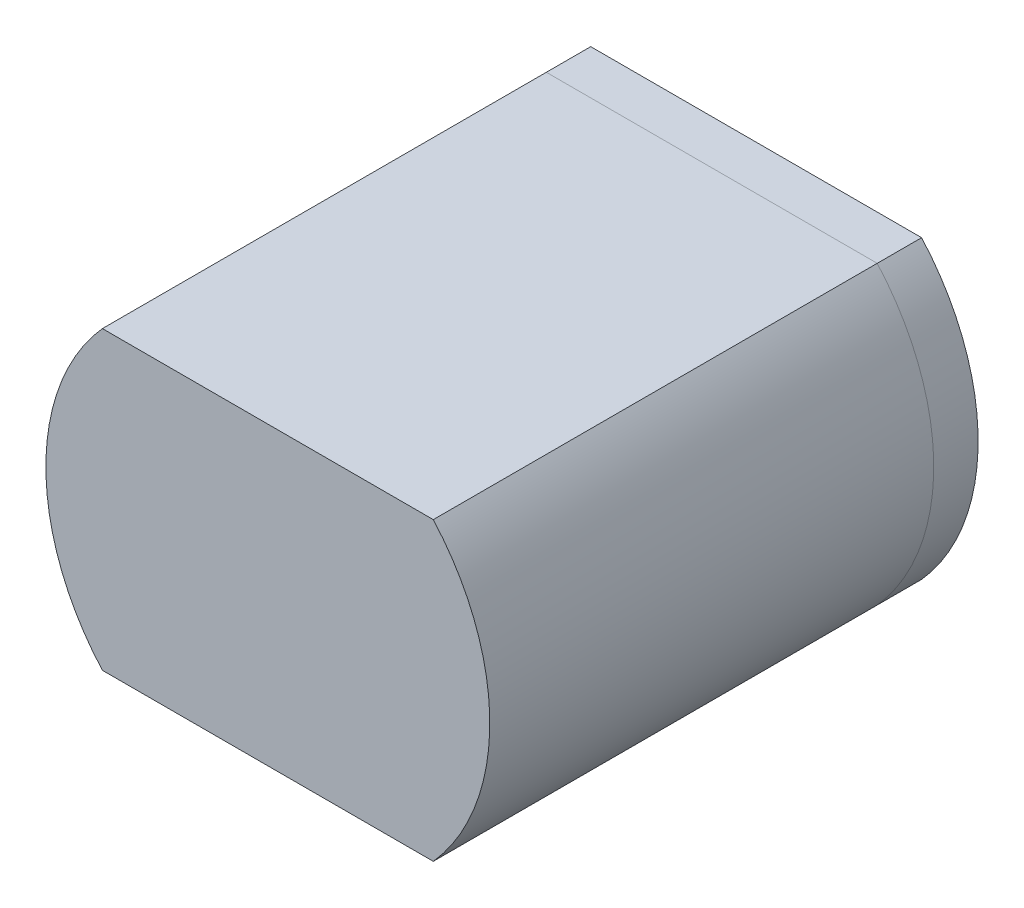
SolidWorks part; units mm, degrees
ref_plane "Front Plane" through (0, 0, 0) normal (0, 0, 1) x (1, 0, 0)
ref_plane "Top Plane" through (0, 0, 0) normal (0, 1, 0) x (1, 0, 0)
ref_plane "Right Plane" through (0, 0, 0) normal (1, 0, 0) x (0, 0, -1)
sketch "Sketch1" plane through (0, 0, 0) normal (0, 0, 1) x (1, 0, 0)
  line L1 (-5.5902, -5) -> (5.5902, -5)
  line L3 (-5.5902, 5) -> (5.5902, 5)
  line L5 (-13.9877, -5) -> (13.9877, 5) construction
  line L6 (-13.9877, 5) -> (13.9877, -5) construction
  arc A0 (-5.5902, 5) -> (-5.5902, -5) centre (0, 0) ccw
  arc A1 (5.5902, -5) -> (5.5902, 5) centre (0, 0) ccw
  dimension "D1" = 10
  dimension "D2" = 15
  dimension "D3" = 5
extrude "Boss-Extrude1" add sketch "Sketch1" along normal blind 15
sketch "Sketch2" plane through (0, 0, 0) normal (0, 0, -1) x (-1, 0, 0)
  line L0 (5.5902, -5) -> (-5.5902, -5) construction
  line L1 (-5.5902, 5) -> (5.5902, 5) construction
  line L2 (5.5902, -5) -> (-5.5902, -5)
  line L3 (-5.5902, 5) -> (5.5902, 5)
  arc A0 (-5.5902, 5) -> (-5.5902, -5) centre (0, 0) ccw construction
  arc A1 (-5.5902, 5) -> (-5.5902, -5) centre (0, 0) ccw
  arc A2 (5.5902, -5) -> (5.5902, 5) centre (0, 0) ccw construction
  arc A3 (5.5902, -5) -> (5.5902, 5) centre (0, 0) ccw
extrude "Boss-Extrude2" add sketch "Sketch2" along normal blind 1.5 separate body
